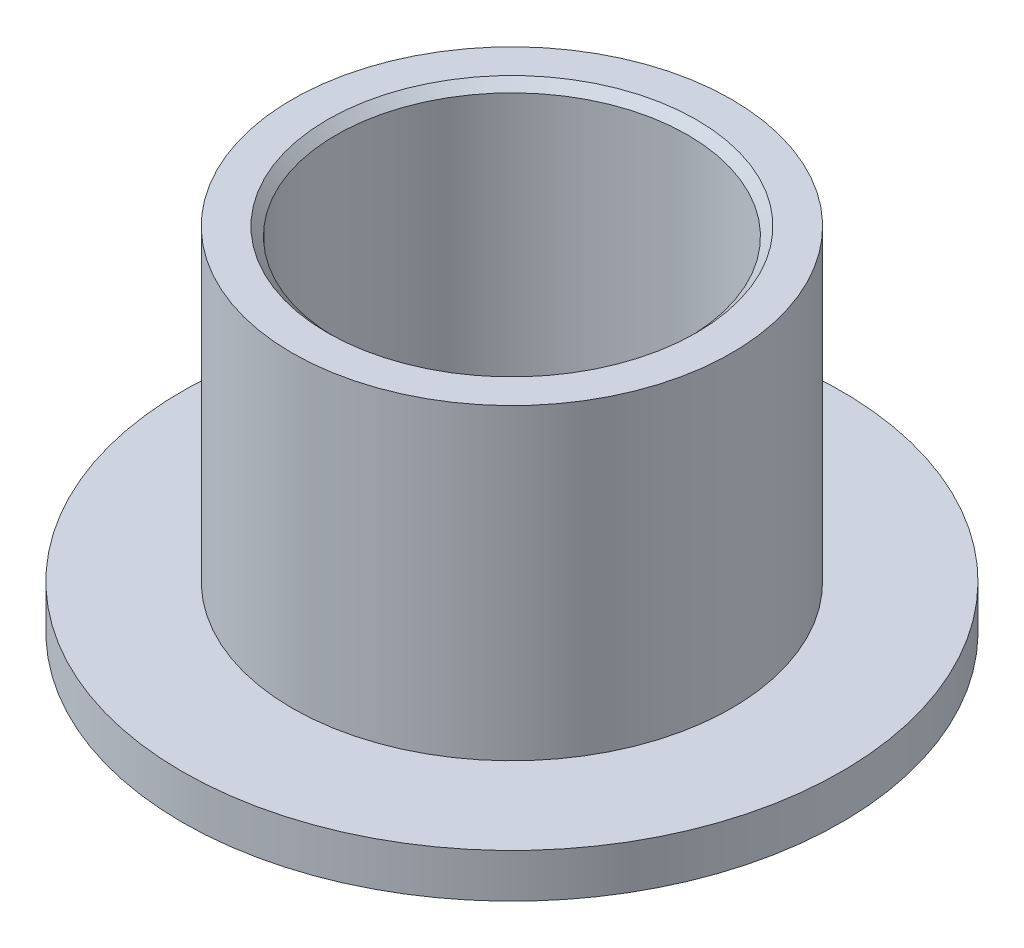
SolidWorks part; units mm, degrees
ref_plane "Ebene vorne" through (0, 0, 0) normal (0, 0, 1) x (1, 0, 0)
ref_plane "Ebene oben" through (0, 0, 0) normal (0, 1, 0) x (1, 0, 0)
ref_plane "Ebene rechts" through (0, 0, 0) normal (1, 0, 0) x (0, 0, -1)
sketch "Skizze1" plane through (0, 0, 0) normal (0, 1, 0) x (1, 0, 0)
  circle A0 centre (0, 0) radius 7.5
  dimension "D1" = 15
extrude "Aufsatz-Linear austragen1" add sketch "Skizze1" along normal blind 1
sketch "Skizze2" plane through (0, 1, 0) normal (0, 1, 0) x (1, 0, 0)
  circle A0 centre (0, 0) radius 5
  dimension "D2" = 10
extrude "Aufsatz-Linear austragen2" add sketch "Skizze2" along normal blind 7
sketch "Skizze4" plane through (0, 8, 0) normal (0, 1, 0) x (1, 0, 0)
  circle A0 centre (0, 0) radius 4
  dimension "D1" = 8
extrude "Schnitt-Linear austragen1" cut sketch "Skizze4" against normal through all
chamfer "Fase1" distance 0.2 angle 45 2 edges at (0, 0, 4) (0, 8, 4)
